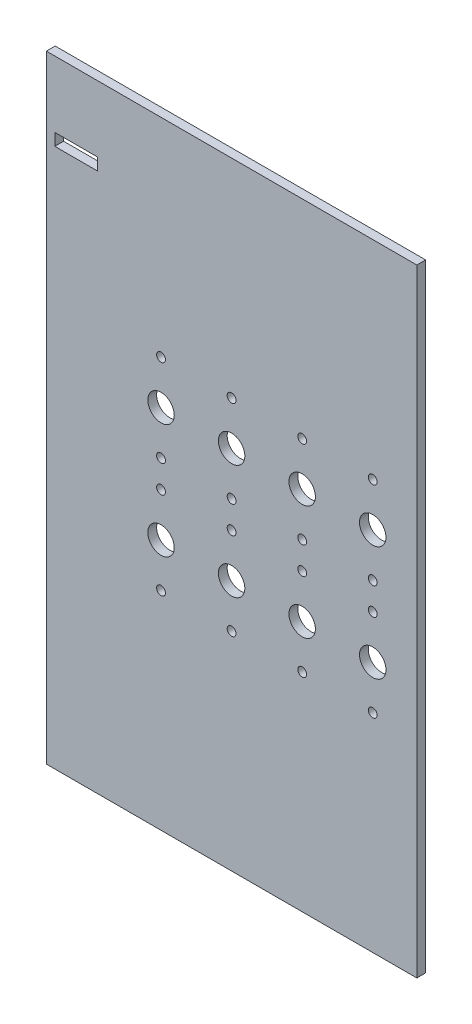
SolidWorks part; units mm, degrees
ref_plane "前视基准面" through (0, 0, 0) normal (0, 0, 1) x (1, 0, 0)
ref_plane "上视基准面" through (0, 0, 0) normal (0, 1, 0) x (1, 0, 0)
ref_plane "右视基准面" through (0, 0, 0) normal (1, 0, 0) x (0, 0, -1)
sketch "草图1" plane through (0, 0, 0) normal (0, 0, 1) x (1, 0, 0)
  line L0 (0, -350) -> (420, -350)
  line L1 (420, -350) -> (420, 350)
  line L2 (420, 350) -> (0, 350)
  line L3 (0, 350) -> (0, -350)
  circle A0 centre (130, 114.5) radius 5
  circle A1 centre (130, 15.5) radius 5
  circle A2 centre (210, 114.5) radius 5
  circle A3 centre (210, 15.5) radius 5
  circle A4 centre (290, 114.5) radius 5
  circle A5 centre (290, 15.5) radius 5
  circle A6 centre (370, 114.5) radius 5
  circle A7 centre (370, 15.5) radius 5
  circle A8 centre (130, 65) radius 15
  circle A9 centre (210, 65) radius 15
  circle A10 centre (290, 65) radius 15
  circle A11 centre (370, 65) radius 15
  circle A12 centre (130, -114.5) radius 5
  circle A13 centre (130, -15.5) radius 5
  circle A14 centre (210, -114.5) radius 5
  circle A15 centre (210, -15.5) radius 5
  circle A16 centre (290, -114.5) radius 5
  circle A17 centre (290, -15.5) radius 5
  circle A18 centre (370, -114.5) radius 5
  circle A19 centre (370, -15.5) radius 5
  circle A20 centre (130, -65) radius 15
  circle A21 centre (210, -65) radius 15
  circle A22 centre (290, -65) radius 15
  circle A23 centre (370, -65) radius 15
extrude "凸台-拉伸1" add sketch "草图1" along normal blind 10
sketch "草图2" plane through (0, 0, 0) normal (0, 0, -1) x (-1, 0, 0)
  line L0 (-420, 350) -> (0, 350) construction
  line L1 (-9.53, 261.29) -> (-57.76, 261.29)
  line L2 (-9.53, 261.29) -> (-9.53, 275)
  line L3 (-9.53, 275) -> (-57.76, 275)
  line L4 (-57.76, 261.29) -> (-57.76, 275)
  line L5 (-9.53, 261.29) -> (-57.76, 275) construction
  line L6 (-9.53, 275) -> (-57.76, 261.29) construction
  line L7 (0, 350) -> (0, -350) construction
  point P0 (-33.645, 268.145)
  dimension "D1" = 48.23
  dimension "D2" = 13.71
  dimension "D3" = 75
  dimension "D4" = 9.53
extrude "切除-拉伸1" cut sketch "草图2" against normal blind 10
